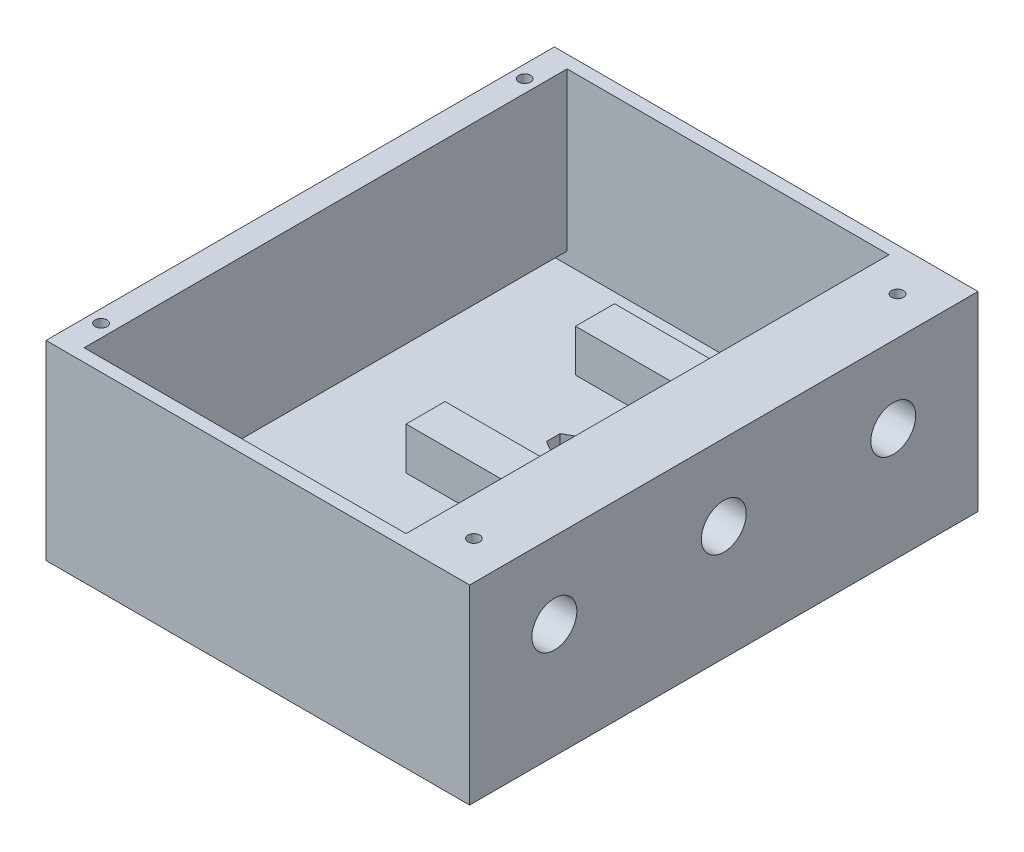
SolidWorks part; units mm, degrees
ref_plane "Спереди" through (0, 0, 0) normal (0, 0, 1) x (1, 0, 0)
ref_plane "Сверху" through (0, 0, 0) normal (0, 1, 0) x (1, 0, 0)
ref_plane "Справа" through (0, 0, 0) normal (1, 0, 0) x (0, 0, -1)
sketch "Sketch1" plane through (0, 0, 0) normal (0, 1, 0) x (1, 0, 0)
  line L1 (50, -60) -> (-50, -60)
  line L2 (50, -60) -> (50, 60)
  line L3 (50, 60) -> (-50, 60)
  line L4 (-50, -60) -> (-50, 60)
  line L5 (50, -60) -> (-50, 60) construction
  line L6 (50, 60) -> (-50, -60) construction
  point P0 (0, 0)
  dimension "D1" = 100
  dimension "D2" = 120
extrude "Boss-Extrude1" add sketch "Sketch1" along normal blind 5
sketch "Sketch2" plane through (0, 5, 0) normal (0, 1, 0) x (1, 0, 0)
  line L1 (50, -60) -> (-50, -60)
  line L2 (50, -60) -> (50, 60)
  line L3 (50, 60) -> (-50, 60)
  line L4 (-50, -60) -> (-50, 60)
  line L5 (50, -60) -> (-50, 60) construction
  line L6 (50, 60) -> (-50, -60) construction
  line L7 (47, -57) -> (-47, -57)
  line L8 (47, -57) -> (47, 57)
  line L9 (47, 57) -> (-47, 57)
  line L10 (-47, -57) -> (-47, 57)
  line L11 (47, -57) -> (-47, 57) construction
  line L12 (47, 57) -> (-47, -57) construction
  point P0 (0, 0)
  point P7 (0, 0)
  dimension "D1" = 3
  dimension "D2" = 3
extrude "Boss-Extrude2" add sketch "Sketch2" along normal blind 40
sketch "Sketch3" plane through (0, 5, 0) normal (0, 1, 0) x (1, 0, 0)
  line L0 (-47, 40) -> (47, 40) construction
  line L1 (-47, 57) -> (-47, -57) construction
  line L2 (47, -57) -> (47, 57) construction
  line L3 (-47, 0) -> (47, 0) construction
  line L4 (0, 40) -> (0, 0) construction
  line L5 (-47, -40) -> (47, -40) construction
  line L6 (0, 0) -> (0, -40) construction
  line L8 (20.4, 35.4) -> (-20.4, 35.4)
  line L9 (20.4, 35.4) -> (20.4, 44.6)
  line L10 (20.4, 44.6) -> (-20.4, 44.6)
  line L11 (-20.4, 35.4) -> (-20.4, 44.6)
  line L12 (20.4, 35.4) -> (-20.4, 44.6) construction
  line L13 (20.4, 44.6) -> (-20.4, 35.4) construction
  line L14 (20.4, -4.6) -> (-20.4, -4.6)
  line L15 (20.4, -4.6) -> (20.4, 4.6)
  line L16 (20.4, 4.6) -> (-20.4, 4.6)
  line L17 (-20.4, -4.6) -> (-20.4, 4.6)
  line L18 (20.4, -4.6) -> (-20.4, 4.6) construction
  line L19 (20.4, 4.6) -> (-20.4, -4.6) construction
  line L20 (20.4, -44.6) -> (-20.4, -44.6)
  line L21 (20.4, -44.6) -> (20.4, -35.4)
  line L22 (20.4, -35.4) -> (-20.4, -35.4)
  line L23 (-20.4, -44.6) -> (-20.4, -35.4)
  line L24 (20.4, -44.6) -> (-20.4, -35.4) construction
  line L25 (20.4, -35.4) -> (-20.4, -44.6) construction
  dimension "D1" = 40
  dimension "D2" = 40.8
  dimension "D3" = 9.2
extrude "Boss-Extrude3" add sketch "Sketch3" along normal blind 10
sketch "Sketch4" plane through (47, 0, 0) normal (-1, 0, 0) x (0, 0, 1)
  line L0 (0, 45) -> (0, 5) construction
  line L1 (57, 45) -> (-57, 45) construction
  line L2 (57, 5) -> (-57, 5) construction
  line L4 (57, 5) -> (-57, 5)
  line L5 (57, 5) -> (57, 45)
  line L6 (57, 45) -> (-57, 45)
  line L7 (-57, 5) -> (-57, 45)
  line L8 (57, 5) -> (-57, 45) construction
  line L9 (57, 45) -> (-57, 5) construction
  point P6 (0, 25)
extrude "Boss-Extrude4" add sketch "Sketch4" along normal blind 15
sketch "Sketch5" plane through (32, 0, 0) normal (-1, 0, 0) x (0, 0, 1)
  line L0 (40, 5) -> (40, 45) construction
  line L1 (-57, 5) -> (57, 5) construction
  line L2 (57, 45) -> (-57, 45) construction
  line L3 (0, 5) -> (0, 45) construction
  line L4 (-40, 5) -> (-40, 45) construction
  line L5 (-40, 25) -> (0, 25) construction
  line L6 (0, 25) -> (40, 25) construction
  line L7 (-40, 27) -> (40, 27) construction
  circle A0 centre (-40, 27) radius 5.3
  circle A1 centre (0, 27) radius 5.3
  circle A2 centre (40, 27) radius 5.3
  dimension "D2" = 10.6
  dimension "D3" = 22
  dimension "D1" = 40
extrude "Cut-Extrude1" cut sketch "Sketch5" against normal up to surface (18 mm away) up to face at (50, 22.5, 0)
sketch "Sketch8" plane through (0, 5, 0) normal (0, 1, 0) x (1, 0, 0)
  line L0 (-7.5, -57) -> (-7.5, 57) construction
  line L1 (-47, -57) -> (32, -57) construction
  line L2 (32, 57) -> (-47, 57) construction
  circle A0 centre (-7.5, -20) radius 1.6
  circle A1 centre (-7.5, 20) radius 1.6
  point P10 (-7.5, 0)
  dimension "D1" = 3.2
  dimension "D2" = 40
  dimension "D3" = 20
extrude "Cut-Extrude2" cut sketch "Sketch8" against normal through all
sketch "Sketch9" plane through (0, 5, 0) normal (0, 1, 0) x (1, 0, 0)
  line L0 (-47, 57) -> (-47, -57) construction
  line L1 (-10.2713, -21.6) -> (-7.5, -23.2)
  line L2 (-7.5, -23.2) -> (-4.7287, -21.6)
  line L3 (-4.7287, -21.6) -> (-4.7287, -18.4)
  line L4 (-4.7287, -18.4) -> (-7.5, -16.8)
  line L5 (-7.5, -16.8) -> (-10.2713, -18.4)
  line L6 (-10.2713, -18.4) -> (-10.2713, -21.6)
  line L7 (-10.2713, 21.6) -> (-10.2713, 18.4)
  line L8 (-10.2713, 18.4) -> (-7.5, 16.8)
  line L9 (-7.5, 16.8) -> (-4.7287, 18.4)
  line L10 (-4.7287, 18.4) -> (-4.7287, 21.6)
  line L11 (-4.7287, 21.6) -> (-7.5, 23.2)
  line L12 (-7.5, 23.2) -> (-10.2713, 21.6)
  circle A0 centre (-7.5, -20) radius 3.2 construction
  circle A1 centre (-7.5, 20) radius 3.2 construction
  dimension "D1" = 6.4
extrude "Cut-Extrude3" cut sketch "Sketch9" against normal blind 3
sketch "Sketch10" plane through (-47, 0, 0) normal (1, 0, 0) x (0, 0, -1)
  line L0 (0, 47.7768) -> (0, 5) construction
  line L1 (57, 5) -> (-57, 5) construction
  line L3 (-57, 7.7768) -> (57, 7.7768)
  line L4 (-57, 7.7768) -> (-57, 45)
  line L5 (-57, 45) -> (57, 45)
  line L6 (57, 7.7768) -> (57, 45)
  line L7 (-57, 7.7768) -> (57, 45) construction
  line L8 (-57, 45) -> (57, 7.7768) construction
  point P4 (0, 26.3884)
extrude "Boss-Extrude6" add sketch "Sketch10" along normal blind 3
sketch "Sketch11" plane through (0, 45, 0) normal (0, 1, 0) x (1, 0, 0)
  line L0 (41, -60) -> (41, 60) construction
  line L1 (-50, -60) -> (50, -60) construction
  line L2 (50, 60) -> (-50, 60) construction
  line L3 (-47, -60) -> (-47, 60) construction
  line L4 (32, -57) -> (32, 57) construction
  line L5 (50, -60) -> (50, 60) construction
  circle A0 centre (41, -50) radius 1.4
  circle A1 centre (41, 50) radius 1.4
  circle A2 centre (-47, 50) radius 1.4
  circle A3 centre (-47, -50) radius 1.4
  point P22 (41, 0)
  point P23 (-47, 0)
  dimension "D8" = 2.8
  dimension "D1" = 9
  dimension "D2" = 18
  dimension "D3" = 3
  dimension "D4" = 100
  dimension "D5" = 50
  dimension "D6" = 100
  dimension "D7" = 50
extrude "Cut-Extrude4" cut sketch "Sketch11" against normal blind 40
sketch "Sketch13" plane through (0, 45, 0) normal (0, 1, 0) x (1, 0, 0)
  line L0 (-50, 60) -> (50, 60) construction
  line L1 (50, 60) -> (50, -60) construction
  line L2 (50, -60) -> (-50, -60) construction
  line L3 (-50, -60) -> (-50, 60) construction
  line L4 (-44, 57) -> (-44, -57) construction
  line L5 (-44, -57) -> (32, -57) construction
  line L6 (32, -57) -> (32, 57) construction
  line L7 (32, 57) -> (-44, 57) construction
  dimension "D1" = 100
  dimension "D2" = 120
  dimension "D3" = 76
  dimension "D4" = 114
  dimension "D5" = 18
  dimension "D6" = 6
  dimension "D7" = 3
sketch "Sketch14" plane through (0, 0, 0) normal (0, -1, 0) x (1, 0, 0)
  line L0 (50, 20) -> (-50, 20) construction
  line L1 (50, 60) -> (50, -60) construction
  line L2 (-50, -60) -> (-50, 60) construction
  line L3 (-50, 60) -> (50, 60) construction
  line L4 (17.6, 12.5) -> (30.4, 12.5)
  line L5 (17.6, 12.5) -> (17.6, 27.5)
  line L6 (17.6, 27.5) -> (30.4, 27.5)
  line L7 (30.4, 12.5) -> (30.4, 27.5)
  line L8 (17.6, 12.5) -> (30.4, 27.5) construction
  line L9 (17.6, 27.5) -> (30.4, 12.5) construction
  point P6 (24, 20)
  dimension "D1" = 15
  dimension "D2" = 12.8
  dimension "D3" = 26
  dimension "D4" = 40
extrude "Cut-Extrude5" cut sketch "Sketch14" against normal up to surface (5 mm away) up to face at (-27.6, 5, 0)
sketch "Sketch15" plane through (0, 5, 0) normal (0, 1, 0) x (1, 0, 0)
  line L0 (30.4, -12.5) -> (30.4, -8.5)
  line L1 (30.4, -8.5) -> (8.4, -8.5)
  line L2 (8.4, -8.5) -> (8.4, -31.5)
  line L3 (8.4, -31.5) -> (30.4, -31.5)
  line L4 (30.4, -31.5) -> (30.4, -27.5)
  line L5 (30.4, -27.5) -> (17.6, -27.5)
  line L6 (17.6, -27.5) -> (17.6, -12.5)
  line L7 (17.6, -12.5) -> (30.4, -12.5)
  dimension "D1" = 4
  dimension "D2" = 22
extrude "Cut-Extrude6" cut sketch "Sketch15" against normal blind 2
